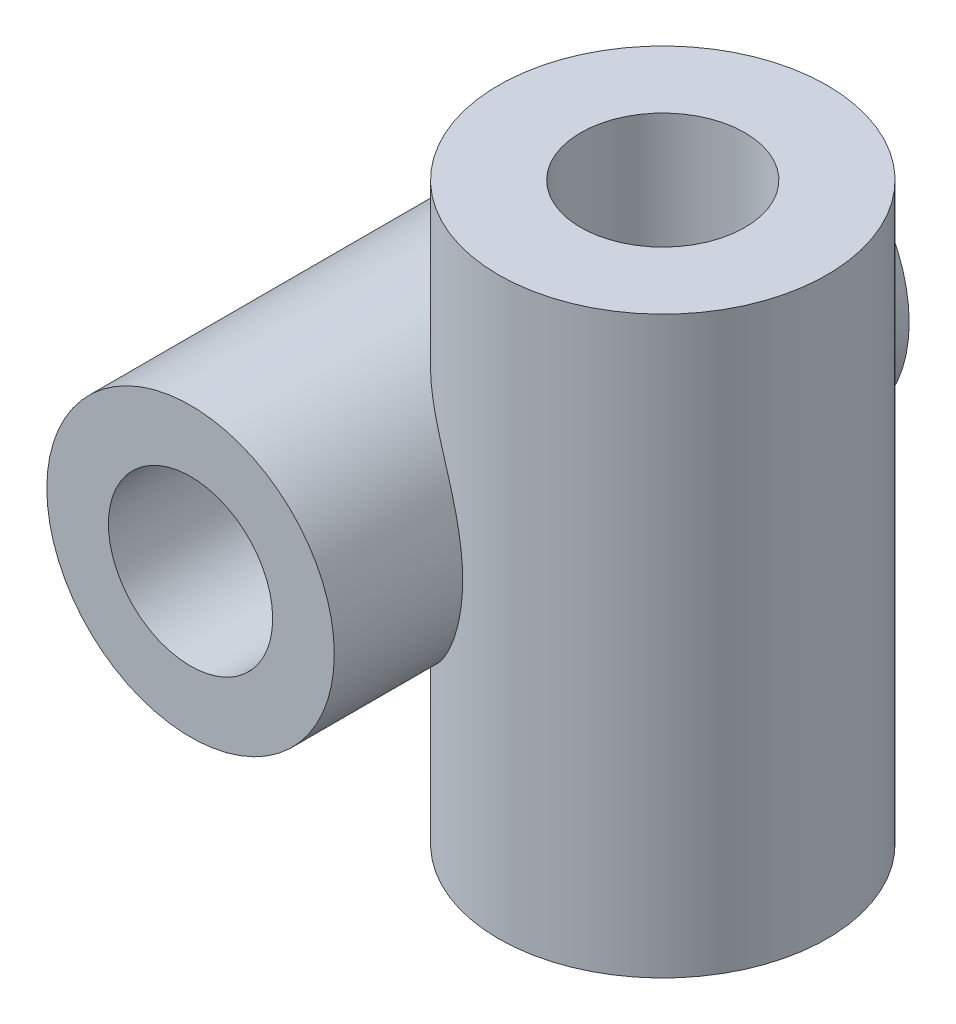
SolidWorks part; units mm, degrees
ref_plane "Front Plane" through (0, 0, 0) normal (0, 0, 1) x (1, 0, 0)
ref_plane "Top Plane" through (0, 0, 0) normal (0, 1, 0) x (1, 0, 0)
ref_plane "Right Plane" through (0, 0, 0) normal (1, 0, 0) x (0, 0, -1)
sketch "Sketch1" plane through (0, 0, 0) normal (0, 0, 1) x (1, 0, 0)
  line L0 (-342.3793, 0) -> (342.3793, 0) construction
  line L1 (0, 75.1599) -> (0, -75.1599) construction
  circle A0 centre (0, 0) radius 14
  circle A1 centre (0, 0) radius 8
  point P4 (0, 0)
  point P7 (0, 0)
  dimension "D1" = 28
  dimension "D2" = 16
extrude "Boss-Extrude1" add sketch "Sketch1" along normal mid plane 56
sketch "Sketch2" plane through (0, 0, 0) normal (0, 0, 1) x (1, 0, 0)
  line L0 (18, -19.9683) -> (18, 19.9683) construction
  line L1 (26, 28) -> (26, -28)
  line L2 (26, -28) -> (34, -28)
  line L3 (34, -28) -> (34, 28)
  line L4 (34, 28) -> (26, 28)
  point P3 (18, 0)
  dimension "D1" = 18
  dimension "D2" = 8
  dimension "D3" = 16
  dimension "D4" = 56
  dimension "D5" = 28
revolve "Revolve1" add sketch "Sketch2" angle 360 about L0
sketch "Sketch3" plane through (0, 0, 28) normal (0, 0, 1) x (1, 0, 0)
  circle A0 centre (0, 0) radius 8 construction
  circle A1 centre (0, 0) radius 8
extrude "Cut-Extrude1" cut sketch "Sketch3" against normal blind 56
sketch "Sketch4" plane through (0, 28, 0) normal (0, 1, 0) x (1, 0, 0)
  circle A0 centre (18, 0) radius 8 construction
  circle A1 centre (18, 0) radius 8
extrude "Cut-Extrude2" cut sketch "Sketch4" against normal blind 56
